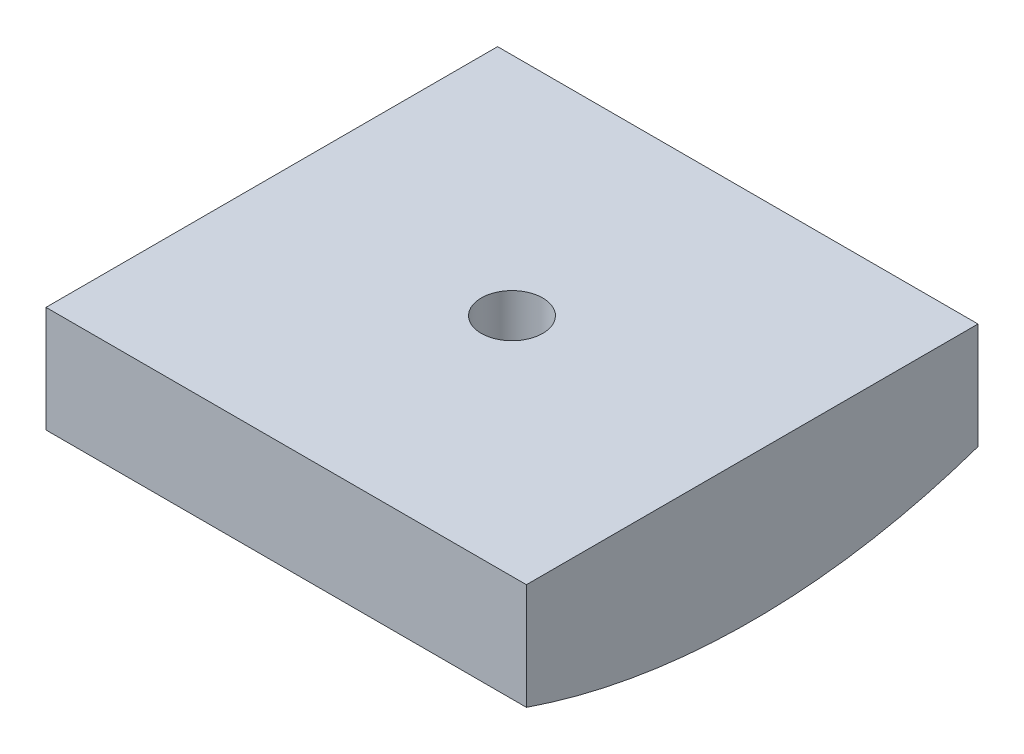
SolidWorks part; units mm, degrees
material "Beech"
ref_plane "Front Plane" through (0, 0, 0) normal (0, 0, 1) x (1, 0, 0)
ref_plane "Top Plane" through (0, 0, 0) normal (0, 1, 0) x (1, 0, 0)
ref_plane "Right Plane" through (0, 0, 0) normal (1, 0, 0) x (0, 0, -1)
sketch "Sketch1" plane through (0, 0, 0) normal (1, 0, 0) x (0, 0, -1)
  line L0 (0, 0) -> (0, -90.5205) construction
  line L1 (-23.5, -57) -> (23.5, -57)
  line L2 (-23.5, -57) -> (-23.5, -68.057)
  line L4 (23.5, -57) -> (23.5, -68.057)
  arc A0 (-23.5, -68.057) -> (23.5, -68.057) centre (0, 0) ccw construction
  arc A1 (-23.5, -68.057) -> (23.5, -68.057) centre (0, 0) ccw
  circle A2 centre (0, 0) radius 72 construction
  point P7 (0, -72)
  dimension "D1" = 144
  dimension "D2" = 15
  dimension "D3" = 47
extrude "Boss-Extrude1" add sketch "Sketch1" along normal blind 50
sketch "Sketch2" plane through (0, -57, 0) normal (0, 1, 0) x (1, 0, 0)
  line L0 (0, 23.5) -> (50, -23.5) construction
  line L1 (0, -23.5) -> (50, 23.5) construction
  line L2 (0, 0) -> (25, 0) construction
  line L3 (0, 23.5) -> (0, -23.5) construction
  circle A0 centre (25, 0) radius 3.2
  dimension "D1" = 6.4
extrude "Cut-Extrude1" cut sketch "Sketch2" against normal through all
